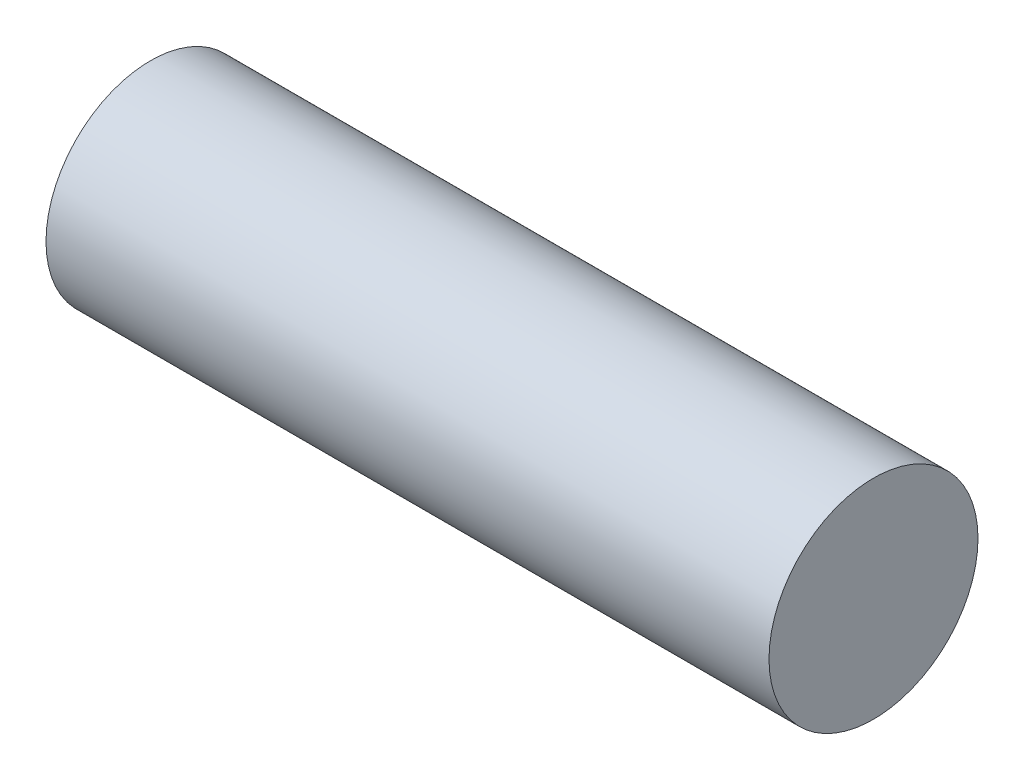
SolidWorks part; units mm, degrees
ref_plane "Front Plane" through (0, 0, 0) normal (0, 0, 1) x (1, 0, 0)
ref_plane "Top Plane" through (0, 0, 0) normal (0, 1, 0) x (1, 0, 0)
ref_plane "Right Plane" through (0, 0, 0) normal (1, 0, 0) x (0, 0, -1)
sketch "Sketch2" plane through (0, 0, 0) normal (0, 0, 1) x (1, 0, 0)
  line L0 (-9.1559, 0) -> (2.7441, 0)
  line L1 (2.7441, 0) -> (2.7441, 1.72)
  line L2 (2.7441, 1.72) -> (-9.1559, 1.72)
  line L3 (-9.1559, 1.72) -> (-9.1559, 0)
  dimension "D1" = 1.72
  dimension "D2" = 11.9
revolve "Revolve1" add sketch "Sketch2" angle 360 about L0
